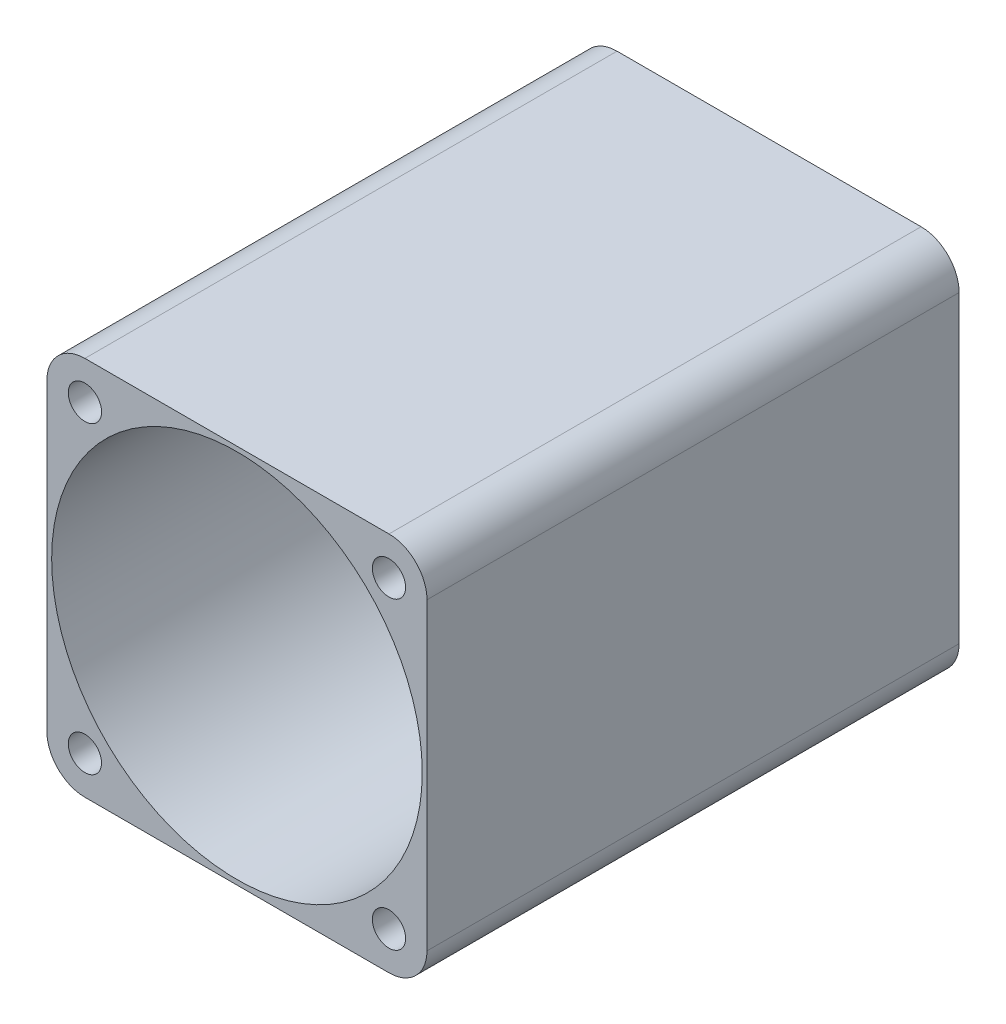
SolidWorks part; units mm, degrees
ref_plane "Front Plane" through (0, 0, 0) normal (0, 0, 1) x (1, 0, 0)
ref_plane "Top Plane" through (0, 0, 0) normal (0, 1, 0) x (1, 0, 0)
ref_plane "Right Plane" through (0, 0, 0) normal (1, 0, 0) x (0, 0, -1)
sketch "Sketch1" plane through (0, 0, 0) normal (0, 0, 1) x (1, 0, 0)
  line L0 (-28.7826, 0) -> (34.8949, 0) construction
  line L1 (-16, -20) -> (16, -20)
  line L2 (-20, -16) -> (-20, 16)
  line L3 (-16, 20) -> (16, 20)
  line L4 (20, -16) -> (20, 16)
  line L5 (-18.8284, -18.8284) -> (18.8284, 18.8284) construction
  line L6 (-18.8284, 18.8284) -> (18.8284, -18.8284) construction
  line L7 (0, -27.7443) -> (0, 25.4975) construction
  circle A0 centre (16, 16) radius 1.75
  circle A2 centre (-16, 16) radius 1.75
  circle A3 centre (16, -16) radius 1.75
  circle A4 centre (-16, -16) radius 1.75
  arc A5 (-16, 20) -> (-20, 16) centre (-16, 16) ccw
  arc A6 (16, 20) -> (20, 16) centre (16, 16) cw
  arc A7 (-16, -20) -> (-20, -16) centre (-16, -16) cw
  arc A8 (16, -20) -> (20, -16) centre (16, -16) ccw
  point P0 (0, 0)
  dimension "D2" = 3.5
  dimension "D1" = 40
  dimension "D3" = 32
  dimension "D4" = 40
  dimension "D5" = 32
  dimension "D6" = 32
extrude "Boss-Extrude1" add sketch "Sketch1" against normal blind 56
sketch "Sketch2" plane through (0, 0, 0) normal (0, 0, 1) x (1, 0, 0)
  circle A0 centre (0, 0) radius 19.5
  point P3 (0, 0)
  dimension "D1" = 39
extrude "Cut-Extrude1" cut sketch "Sketch2" against normal blind 56
sketch "Sketch3" plane through (0, 0, 0) normal (0, 0, 1) x (1, 0, 0)
  line L1 (-19.5, -19.5) -> (19.5, -19.5)
  line L2 (-19.5, -19.5) -> (-19.5, 19.5)
  line L3 (-19.5, 19.5) -> (19.5, 19.5)
  line L4 (19.5, -19.5) -> (19.5, 19.5)
  line L5 (-19.5, -19.5) -> (19.5, 19.5) construction
  line L6 (-19.5, 19.5) -> (19.5, -19.5) construction
  point P0 (0, 0)
  dimension "D1" = 39
  dimension "D2" = 39
ref_plane "Plane1" through (0, 0, -56) normal (0, 0, -1) x (-1, 0, 0)
sketch "Sketch5" plane through (0, 0, -56) normal (0, 0, -1) x (-1, 0, 0)
  line L1 (-19.5, -19.5) -> (19.5, -19.5)
  line L2 (-19.5, -19.5) -> (-19.5, 19.5)
  line L3 (-19.5, 19.5) -> (19.5, 19.5)
  line L4 (19.5, -19.5) -> (19.5, 19.5)
  line L5 (-19.5, -19.5) -> (19.5, 19.5) construction
  line L6 (-19.5, 19.5) -> (19.5, -19.5) construction
  point P0 (0, 0)
  dimension "D1" = 39
  dimension "D2" = 39
